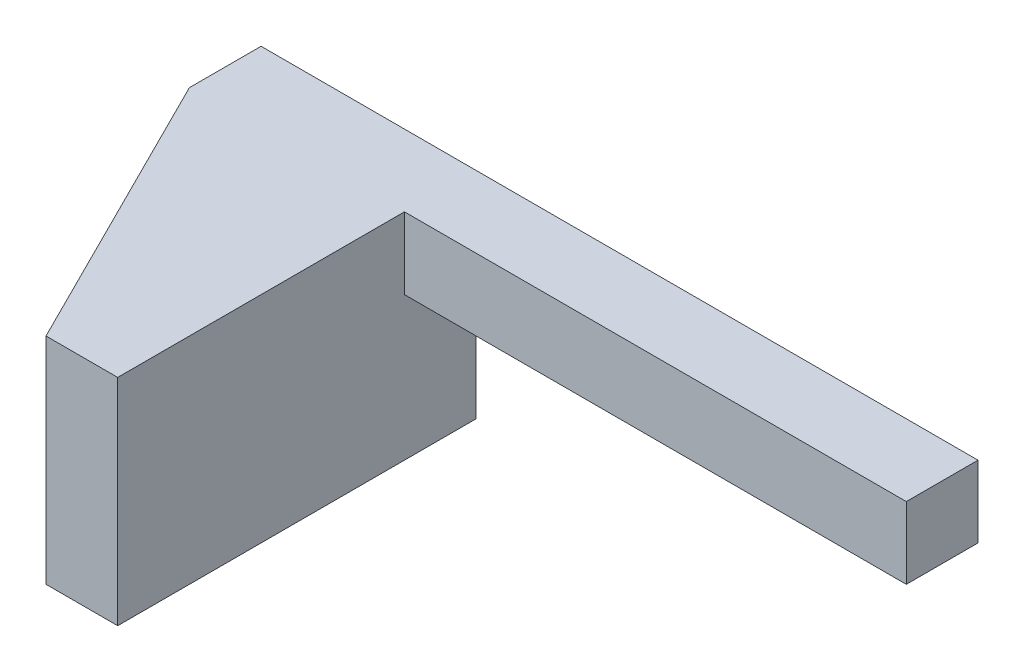
SolidWorks part; units mm, degrees
ref_plane "Plan de face" through (0, 0, 0) normal (0, 0, 1) x (1, 0, 0)
ref_plane "Plan de dessus" through (0, 0, 0) normal (0, 1, 0) x (1, 0, 0)
ref_plane "Plan de droite" through (0, 0, 0) normal (1, 0, 0) x (0, 0, -1)
sketch "Esquisse1" plane through (0, 0, 0) normal (0, 1, 0) x (1, 0, 0)
  line L0 (0, 0) -> (-50, 0)
  line L1 (-50, 0) -> (-50, -5)
  line L2 (-50, -5) -> (-40, -25)
  line L3 (-40, -25) -> (-35, -25)
  line L4 (-35, -25) -> (-35, -5)
  line L5 (-35, -5) -> (0, -5)
  line L6 (0, -5) -> (0, 0)
  dimension "D1" = 35
  dimension "D2" = 20
  dimension "D3" = 5
  dimension "D4" = 5
  dimension "D5" = 5
  dimension "D6" = 15
extrude "Boss.-Extru.1" add sketch "Esquisse1" along normal blind 15
sketch "Esquisse2" plane through (0, 0, 5) normal (0, 0, 1) x (1, 0, 0)
  line L0 (-35, 15) -> (-35, 0) construction
  line L1 (0, 0) -> (-35, 0)
  line L2 (0, 0) -> (0, 10)
  line L3 (0, 10) -> (-35, 10)
  line L4 (-35, 0) -> (-35, 10)
  dimension "D1" = 10
extrude "Enlèv. mat.-Extru.1" cut sketch "Esquisse2" against normal through all both and the other way through all
